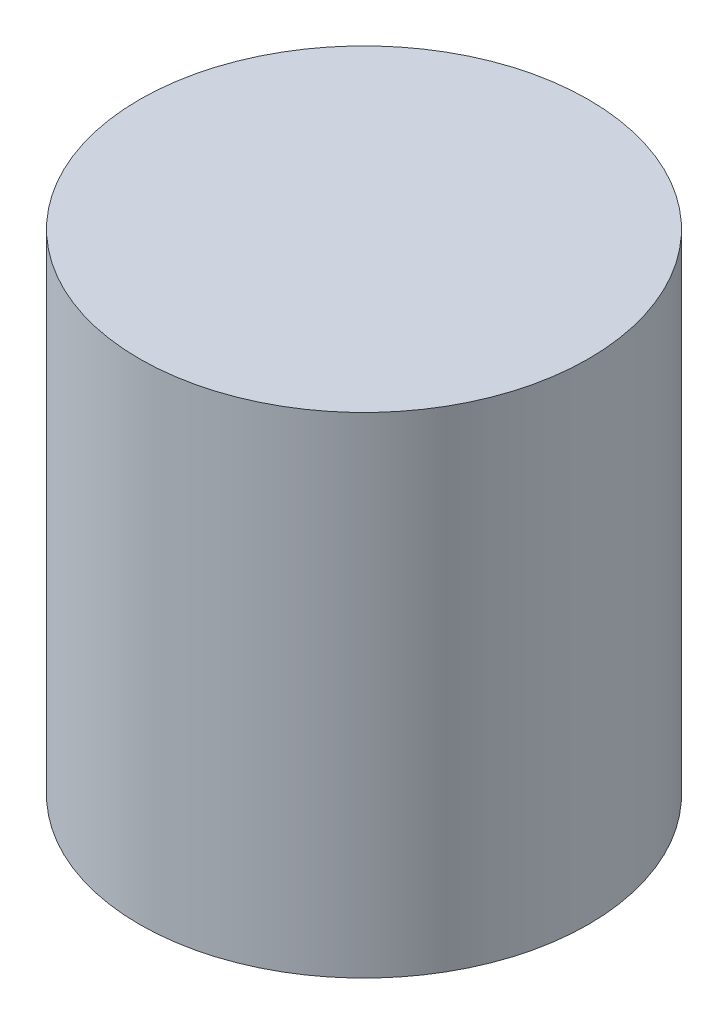
SolidWorks part; units mm, degrees
ref_plane "Front Plane" through (0, 0, 0) normal (0, 0, 1) x (1, 0, 0)
ref_plane "Top Plane" through (0, 0, 0) normal (0, 1, 0) x (1, 0, 0)
ref_plane "Right Plane" through (0, 0, 0) normal (1, 0, 0) x (0, 0, -1)
sketch "Sketch1" plane through (0, 0, 0) normal (0, 1, 0) x (1, 0, 0)
  circle A0 centre (0, 0) radius 5.5
  dimension "D1" = 11
extrude "Boss-Extrude1" add sketch "Sketch1" along normal blind 12
sketch "Sketch2" plane through (0, 0, 0) normal (0, -1, 0) x (1, 0, 0)
  circle A0 centre (0, 0) radius 3
extrude "Cut-Extrude1" cut sketch "Sketch2" against normal blind 5
sketch "Sketch3" plane through (0, 12, 0) normal (0, 1, 0) x (1, 0, 0)
  point P0 (0, 0)
